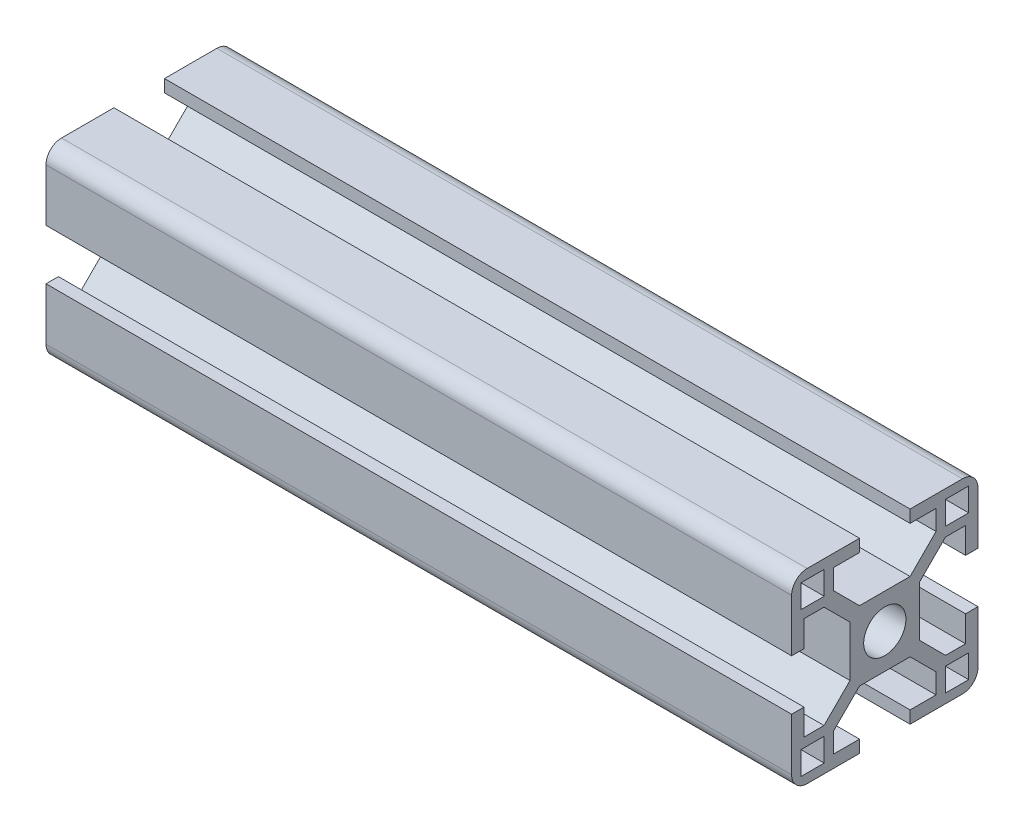
SolidWorks part; units mm, degrees
material "6061 Alloy"
material "6061 Alloy"
ref_plane "Front Plane" through (0, 0, 0) normal (0, 0, 1) x (1, 0, 0)
ref_plane "Top Plane" through (0, 0, 0) normal (0, 1, 0) x (1, 0, 0)
ref_plane "Right Plane" through (0, 0, 0) normal (1, 0, 0) x (0, 0, -1)
sketch "Sketch1" plane through (0, 0, 0) normal (0, 1, 0) x (1, 0, 0)
  line L0 (0, 0) -> (120, 0)
  dimension "D1" = 120
other "T-slot profiles 3030_2(1)"
ref_plane "Plane1" through (0, 0, 0) normal (1, 0, 0) x (0, 0, -1)
sketch "Sketch11" plane through (0, 0, 0) normal (1, 0, 0) x (0, 0, -1)
  line L0 (0, 15) -> (0, -15) construction
  line L1 (-15, -15) -> (15, -15) construction
  line L2 (-15, -15) -> (-15, 15) construction
  line L3 (-15, 15) -> (15, 15) construction
  line L4 (15, -15) -> (15, 15) construction
  line L5 (-15, -15) -> (15, 15) construction
  line L6 (-15, 15) -> (15, -15) construction
  line L7 (-4.07, 5.6) -> (4.07, 5.6)
  line L8 (0, 0) -> (15, 0) construction
  line L9 (-4.07, -5.6) -> (4.07, -5.6)
  line L10 (5.6, -4.07) -> (5.6, 4.07)
  line L11 (-5.6, -4.07) -> (-5.6, 4.07)
  line L12 (-4.07, 5.6) -> (-8.25, 9.78)
  line L13 (4.07, 5.6) -> (8.25, 9.78)
  line L14 (-8.25, 9.78) -> (8.25, 9.78) construction
  line L15 (8.25, 9.78) -> (8.25, 13)
  line L16 (8.25, 13) -> (4.07, 13)
  line L17 (4.07, 13) -> (4.07, 15)
  line L18 (4.07, 15) -> (12.5, 15)
  line L19 (15, 12.5) -> (15, 4.07)
  line L20 (9.78, 8.25) -> (13, 8.25)
  line L21 (13, 8.25) -> (13, 4.07)
  line L22 (9.78, 8.25) -> (5.6, 4.07)
  line L23 (8.25, 9.78) -> (9.78, 8.25) construction
  line L24 (13, 4.07) -> (15, 4.07)
  line L25 (5.6, -4.07) -> (9.78, -8.25)
  line L26 (9.75, 13.5) -> (13.5, 13.5)
  line L27 (9.75, 13.5) -> (9.75, 9.75)
  line L28 (9.75, 9.75) -> (13.5, 9.75)
  line L29 (13.5, 13.5) -> (13.5, 9.75)
  line L30 (9.75, 13.5) -> (13.5, 9.75) construction
  line L31 (9.75, 9.75) -> (13.5, 13.5) construction
  line L32 (9.78, -8.25) -> (13, -8.25)
  line L33 (13, -8.25) -> (13, -4.07)
  line L34 (13, -4.07) -> (15, -4.07)
  line L35 (15, -4.07) -> (15, -12.5)
  line L36 (4.07, -5.6) -> (8.25, -9.78)
  line L37 (8.25, -9.78) -> (8.25, -13)
  line L38 (8.25, -13) -> (4.07, -13)
  line L39 (4.07, -13) -> (4.07, -15)
  line L40 (4.07, -15) -> (12.5, -15)
  line L41 (-4.07, -5.6) -> (-8.25, -9.78)
  line L42 (-8.25, -9.78) -> (-8.25, -13)
  line L43 (-8.25, -13) -> (-4.07, -13)
  line L44 (-4.07, -13) -> (-4.07, -15)
  line L45 (-4.07, -15) -> (-12.5, -15)
  line L46 (-8.25, 9.78) -> (-8.25, 13)
  line L47 (-8.25, 13) -> (-4.07, 13)
  line L48 (-4.07, 13) -> (-4.07, 15)
  line L49 (-4.07, 15) -> (-12.5, 15)
  line L50 (-5.6, 4.07) -> (-9.78, 8.25)
  line L51 (-9.78, 8.25) -> (-13, 8.25)
  line L52 (-13, 8.25) -> (-13, 4.07)
  line L53 (-13, 4.07) -> (-15, 4.07)
  line L54 (-15, 4.07) -> (-15, 12.5)
  line L55 (-5.6, -4.07) -> (-9.78, -8.25)
  line L56 (-9.78, -8.25) -> (-13, -8.25)
  line L57 (-13, -8.25) -> (-13, -4.07)
  line L58 (-13, -4.07) -> (-15, -4.07)
  line L59 (-15, -4.07) -> (-15, -12.5)
  line L60 (9.75, -9.75) -> (13.5, -9.75)
  line L61 (13.5, -13.5) -> (13.5, -9.75)
  line L62 (9.75, -13.5) -> (13.5, -13.5)
  line L63 (9.75, -13.5) -> (9.75, -9.75)
  line L64 (-9.75, 9.75) -> (-13.5, 9.75)
  line L65 (-13.5, 13.5) -> (-13.5, 9.75)
  line L66 (-9.75, 13.5) -> (-13.5, 13.5)
  line L67 (-9.75, 13.5) -> (-9.75, 9.75)
  line L68 (-9.75, -13.5) -> (-9.75, -9.75)
  line L69 (-9.75, -13.5) -> (-13.5, -13.5)
  line L70 (-13.5, -13.5) -> (-13.5, -9.75)
  line L71 (-9.75, -9.75) -> (-13.5, -9.75)
  arc A0 (-15, 12.5) -> (-12.5, 15) centre (-12.5, 12.5) cw
  arc A1 (12.5, -15) -> (15, -12.5) centre (12.5, -12.5) ccw
  arc A2 (15, 12.5) -> (12.5, 15) centre (12.5, 12.5) ccw
  arc A3 (-12.5, -15) -> (-15, -12.5) centre (-12.5, -12.5) cw
  circle A4 centre (0, 0) radius 3.4
  point P0 (0, 0)
  point P6 (0, 0)
  point P7 (-12.5, 12.5)
  point P26 (0, 5.6)
  point P32 (5.6, 0)
  point P44 (11.625, 11.625)
  dimension "D4" = 6.8
  dimension "D3" = 2.5
  dimension "D1" = 30
  dimension "D2" = 30
  dimension "D5" = 8.14
  dimension "D6" = 9.4
  dimension "D7" = 8.14
  dimension "D8" = 9.4
  dimension "D9" = 16.5
  dimension "D10" = 2
  dimension "D11" = 2
  dimension "D12" = 3.75
  dimension "D13" = 3.75
  dimension "D14" = 1.5
  dimension "D15" = 2
  dimension "D16" = 2
  dimension "D17" = 2
  dimension "D18" = 2
  dimension "D19" = 2
  dimension "D20" = 2
